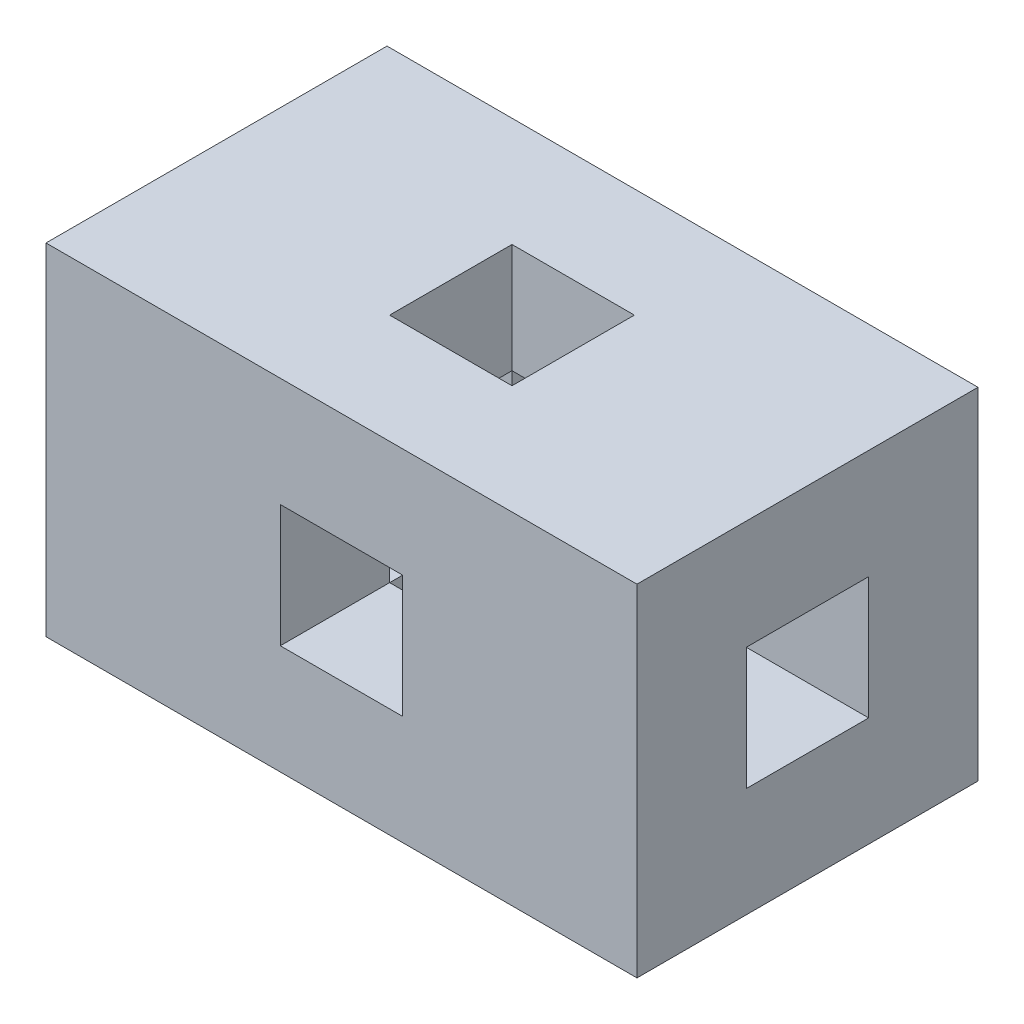
SolidWorks part; units mm, degrees
material "Pine"
ref_plane "Front Plane" through (0, 0, 0) normal (0, 0, 1) x (1, 0, 0)
ref_plane "Top Plane" through (0, 0, 0) normal (0, 1, 0) x (1, 0, 0)
ref_plane "Right Plane" through (0, 0, 0) normal (1, 0, 0) x (0, 0, -1)
sketch "Sketch1" plane through (0, 0, 0) normal (0, 1, 0) x (1, 0, 0)
  line L0 (37.4142, 0) -> (-37.4142, 0) construction
  line L5 (37.4142, -21.59) -> (-37.4142, -21.59)
  line L6 (37.4142, -21.59) -> (37.4142, 21.59)
  line L7 (37.4142, 21.59) -> (-37.4142, 21.59)
  line L8 (-37.4142, -21.59) -> (-37.4142, 21.59)
  point P6 (0, 0)
  point P7 (0, 0)
  point P8 (0, 0)
  dimension "D1" = 74.8284
  dimension "D2" = 43.18
extrude "Boss-Extrude1" add sketch "Sketch1" along normal mid plane 43.18
sketch "Sketch12" plane through (0, 21.59, 0) normal (0, 1, 0) x (1, 0, 0)
  line L1 (-7.747, 7.747) -> (7.747, 7.747)
  line L2 (-7.747, 7.747) -> (-7.747, -7.747)
  line L3 (-7.747, -7.747) -> (7.747, -7.747)
  line L4 (7.747, 7.747) -> (7.747, -7.747)
  line L5 (-7.747, 7.747) -> (7.747, -7.747) construction
  line L6 (-7.747, -7.747) -> (7.747, 7.747) construction
  point P0 (0, 0)
  dimension "D1" = 15.494
  dimension "D2" = 15.494
extrude "Cut-Extrude1" cut sketch "Sketch12" against normal through all
sketch "Sketch15" plane through (0, 0, 21.59) normal (0, 0, 1) x (1, 0, 0)
  line L1 (-7.747, 7.747) -> (7.747, 7.747)
  line L2 (-7.747, 7.747) -> (-7.747, -7.747)
  line L3 (-7.747, -7.747) -> (7.747, -7.747)
  line L4 (7.747, 7.747) -> (7.747, -7.747)
  line L5 (-7.747, 7.747) -> (7.747, -7.747) construction
  line L6 (-7.747, -7.747) -> (7.747, 7.747) construction
  point P0 (0, 0)
  dimension "D1" = 15.494
  dimension "D2" = 15.494
extrude "Cut-Extrude2" cut sketch "Sketch15" against normal through all
sketch "Sketch16" plane through (37.4142, 0, 0) normal (1, 0, 0) x (0, 0, -1)
  line L1 (-7.747, 7.747) -> (7.747, 7.747)
  line L2 (-7.747, 7.747) -> (-7.747, -7.747)
  line L3 (-7.747, -7.747) -> (7.747, -7.747)
  line L4 (7.747, 7.747) -> (7.747, -7.747)
  line L5 (-7.747, 7.747) -> (7.747, -7.747) construction
  line L6 (-7.747, -7.747) -> (7.747, 7.747) construction
  point P0 (0, 0)
  dimension "D1" = 15.494
  dimension "D2" = 15.494
extrude "Cut-Extrude3" cut sketch "Sketch16" against normal through all
